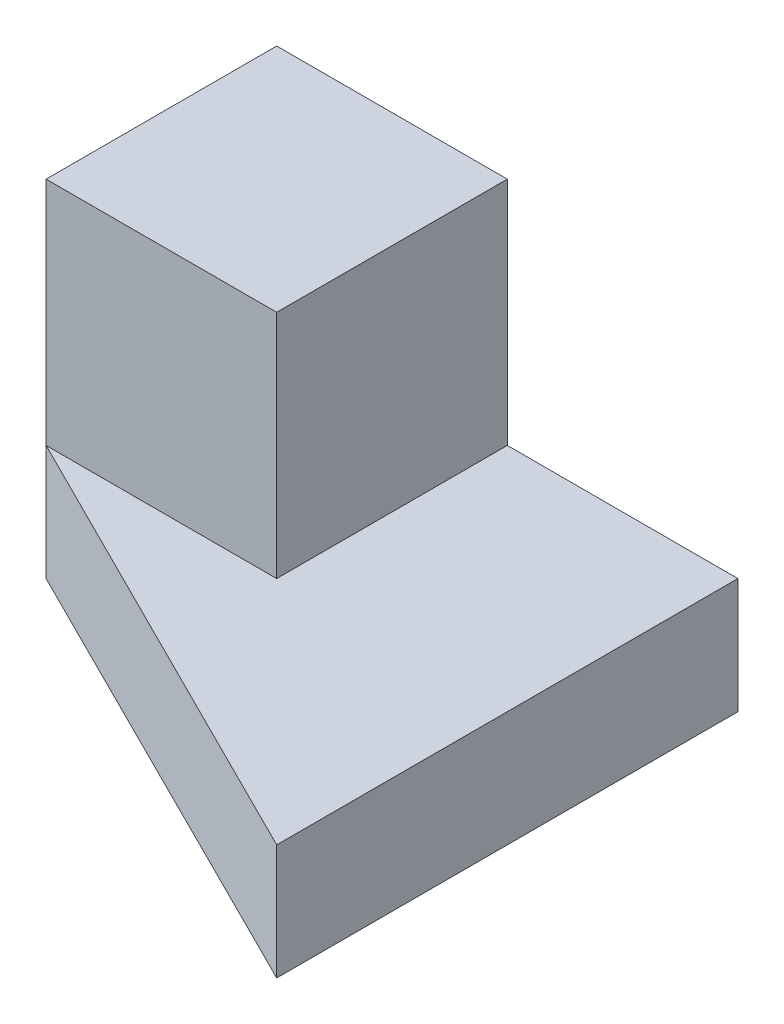
SolidWorks part; units mm, degrees
ref_plane "Front Plane" through (0, 0, 0) normal (0, 0, 1) x (1, 0, 0)
ref_plane "Top Plane" through (0, 0, 0) normal (0, 1, 0) x (1, 0, 0)
ref_plane "Right Plane" through (0, 0, 0) normal (1, 0, 0) x (0, 0, -1)
sketch "Sketch1" plane through (0, 0, 0) normal (0, 1, 0) x (1, 0, 0)
  line L0 (0, 20) -> (0, -20)
  line L1 (0, 20) -> (-40, 20)
  line L2 (-40, 20) -> (-40, 0)
  line L3 (-40, 0) -> (0, -20)
  point P4 (0, 0)
  dimension "D1" = 40
  dimension "D2" = 40
  dimension "D3" = 20
extrude "Boss-Extrude1" add sketch "Sketch1" along normal blind 10 contours L2 L3 L0 L1
sketch "Sketch2" plane through (0, 10, 0) normal (0, 1, 0) x (1, 0, 0)
  line L0 (-40, 20) -> (-20, 20)
  line L1 (0, 20) -> (-40, 20) construction
  line L2 (-20, 20) -> (-20, 0)
  line L3 (-20, 0) -> (-40, 0)
  line L4 (-40, 20) -> (-40, 0)
extrude "Boss-Extrude2" add sketch "Sketch2" along normal blind 20 contours L3 L4 L0 L2
